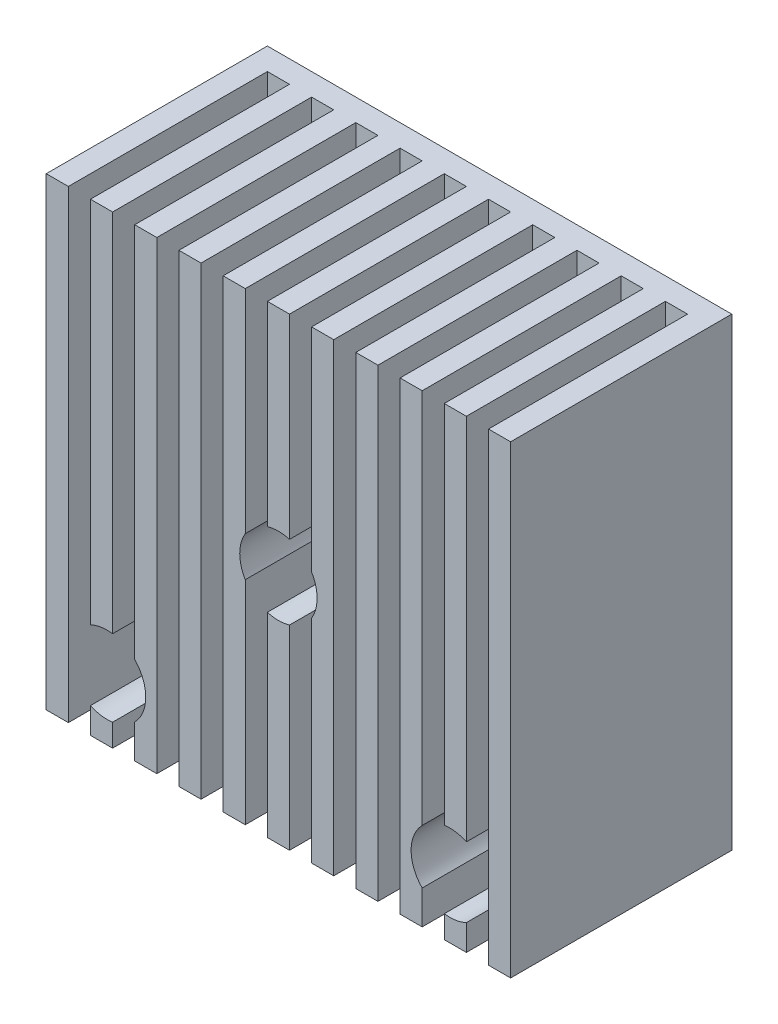
SolidWorks part; units mm, degrees
ref_plane "Front Plane" through (0, 0, 0) normal (0, 0, 1) x (1, 0, 0)
ref_plane "Top Plane" through (0, 0, 0) normal (0, 1, 0) x (1, 0, 0)
ref_plane "Right Plane" through (0, 0, 0) normal (1, 0, 0) x (0, 0, -1)
sketch "Sketch1" plane through (0, 0, 0) normal (0, 0, 1) x (1, 0, 0)
  line L1 (0, 0) -> (42, 0)
  line L2 (0, 0) -> (0, 42)
  line L3 (0, 42) -> (42, 42)
  line L4 (42, 0) -> (42, 42)
  dimension "D1" = 42
  dimension "D2" = 42
extrude "Boss-Extrude1" add sketch "Sketch1" along normal blind 20
sketch "Sketch7" plane through (0, 42, 0) normal (0, 1, 0) x (1, 0, 0)
  line L0 (42, -2) -> (42, -20)
  line L1 (42, -20) -> (42, 0) construction
  line L2 (42, -20) -> (40, -20)
  line L3 (42, -20) -> (0, -20) construction
  line L4 (40, -20) -> (40, -2)
  line L5 (40, -2) -> (38, -2)
  line L6 (42, 0) -> (0, 0) construction
  line L7 (38, -2) -> (38, -20)
  line L8 (38, -20) -> (36, -20)
  line L9 (36, -20) -> (36, -2)
  line L10 (36, -2) -> (34, -2)
  line L11 (34, -2) -> (34, -20)
  line L12 (34, -20) -> (32, -20)
  line L13 (32, -20) -> (32, -2)
  line L14 (32, -2) -> (30, -2)
  line L15 (30, -2) -> (30, -20)
  line L16 (30, -20) -> (28, -20)
  line L17 (28, -20) -> (28, -2)
  line L18 (28, -2) -> (26, -2)
  line L19 (26, -2) -> (26, -20)
  line L20 (26, -20) -> (24, -20)
  line L21 (24, -20) -> (24, -2)
  line L22 (24, -2) -> (22, -2)
  line L23 (22, -2) -> (22, -20)
  line L24 (22, -20) -> (20, -20)
  line L25 (20, -20) -> (20, -2)
  line L26 (20, -2) -> (18, -2)
  line L27 (18, -2) -> (18, -20)
  line L28 (18, -20) -> (16, -20)
  line L29 (16, -20) -> (16, -2)
  line L30 (16, -2) -> (14, -2)
  line L31 (14, -2) -> (14, -20)
  line L32 (14, -20) -> (12, -20)
  line L33 (12, -20) -> (12, -2)
  line L34 (12, -2) -> (10, -2)
  line L35 (10, -2) -> (10, -20)
  line L36 (10, -20) -> (8, -20)
  line L37 (8, -20) -> (8, -2)
  line L38 (8, -2) -> (6, -2)
  line L39 (6, -2) -> (6, -20)
  line L40 (6, -20) -> (4, -20)
  line L41 (4, -20) -> (4, -2)
  line L42 (4, -2) -> (2, -2)
  line L43 (2, -2) -> (2, -20)
  line L44 (2, -20) -> (0, -20)
  line L45 (0, -20) -> (0, -2)
  line L46 (0, -20) -> (0, 0) construction
  dimension "D1" = 2
  dimension "D2" = 2
  dimension "D3" = 2
  dimension "D4" = 10
extrude "Cut-Extrude6" cut sketch "Sketch7" along direction (0, -1, 0) on the side against the normal blind 42 and the other way through all
sketch "Sketch8" plane through (0, 0, 0) normal (0, 0, -1) x (-1, 0, 0)
  line L0 (0, 0) -> (-42, 0) construction
  line L1 (-42, 0) -> (-42, 42) construction
  line L2 (-21, 42) -> (-21, 0) construction
  line L3 (-42, 42) -> (0, 42) construction
  line L4 (-42, 21) -> (0, 21) construction
  line L5 (0, 42) -> (0, 0) construction
  circle A0 centre (-36.5, 5.5) radius 1.6
  circle A1 centre (-5.5, 5.5) radius 1.6
  circle A2 centre (-21, 21) radius 3.5
  dimension "D3" = 3.2
  dimension "D4" = 7
  dimension "D1" = 5.5
  dimension "D2" = 5.5
extrude "Cut-Extrude7" cut sketch "Sketch8" against normal blind 2
sketch "Sketch10" plane through (0, 0, 20) normal (0, 0, 1) x (1, 0, 0)
  line L0 (21, 42) -> (21, 0) construction
  line L1 (22, 42) -> (20, 42) construction
  line L2 (20, 0) -> (22, 0) construction
  circle A0 centre (36.5, 5.5) radius 3.5
  circle A1 centre (5.5, 5.5) radius 3.5
  circle A2 centre (21, 21) radius 3.5
  dimension "D1" = 7
  dimension "D2" = 7
extrude "Cut-Extrude8" cut sketch "Sketch10" against normal blind 18
